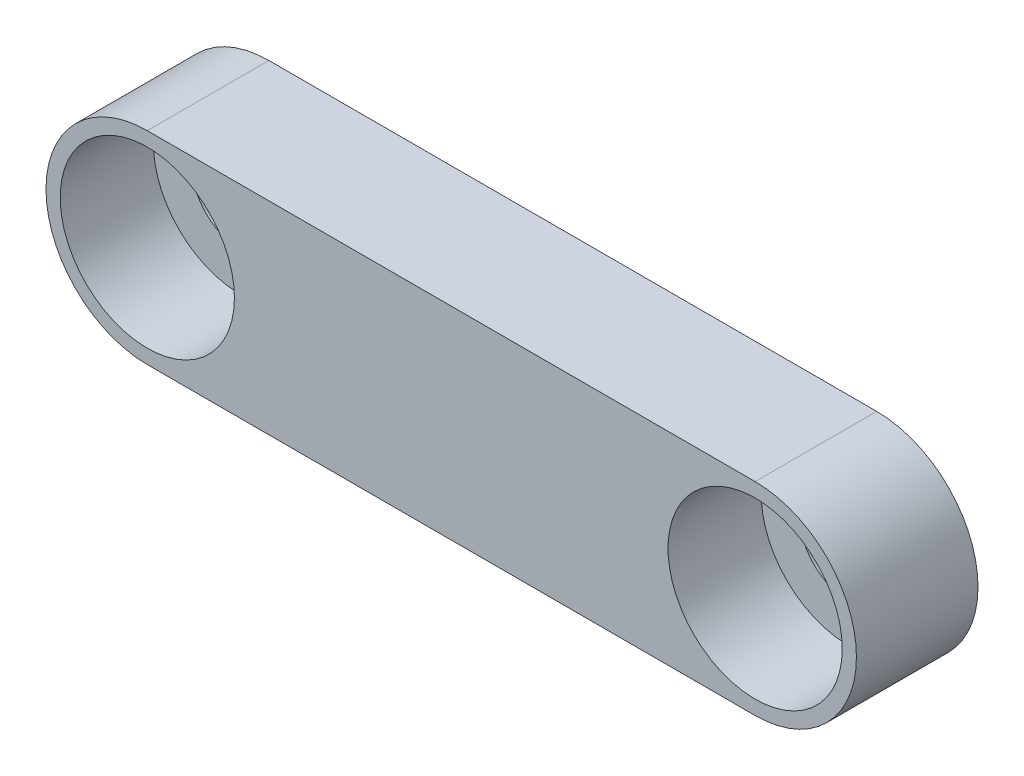
SolidWorks part; units mm, degrees
material "PLA MATTE"
ref_plane "前视基准面" through (0, 0, 0) normal (0, 0, 1) x (1, 0, 0)
ref_plane "上视基准面" through (0, 0, 0) normal (0, 1, 0) x (1, 0, 0)
ref_plane "右视基准面" through (0, 0, 0) normal (1, 0, 0) x (0, 0, -1)
sketch "草图1" plane through (0, 0, 0) normal (0, 0, 1) x (1, 0, 0)
  line L0 (-7.5, 0) -> (7.5, 0) construction
  line L1 (-7.5, 2.5) -> (7.5, 2.5)
  line L2 (-7.5, -2.5) -> (7.5, -2.5)
  arc A0 (-7.5, 2.5) -> (-7.5, -2.5) centre (-7.5, 0) ccw
  arc A1 (7.5, -2.5) -> (7.5, 2.5) centre (7.5, 0) ccw
  point P2 (0, 0)
  dimension "D1" = 15
  dimension "D2" = 5
extrude "凸台-拉伸1" add sketch "草图1" along normal blind 3
hole_wizard "打孔尺寸(%根据)内六角圆柱头螺钉的类型1" positions "草图2" profile "草图3" counterbore size "M2" standard "GB"
sketch "草图2" plane through (0, 0, 3) normal (0, 0, 1) x (1, 0, 0)
  point P0 (-7.5, 0)
  point P3 (7.5, 0)
sketch "草图3" plane through (-7.5, 0, 3) normal (1, 0, 0) x (0, -1, 0)
  line L0 (0, 0) -> (0, 5.921)
  line L1 (0, 5.921) -> (1.2, 5.2)
  line L2 (1.2, 5.2) -> (1.2, 2.3)
  line L3 (1.2, 2.3) -> (2.15, 2.3)
  line L4 (2.15, 2.3) -> (2.15, 0)
  line L5 (2.15, 0) -> (0, 0)
  line L10 (0, 5.921) -> (-1.2, 5.2) construction
  line L11 (0, -6.35) -> (0, 107.95) construction
  dimension "孔直径" = 2.4
  dimension "孔深度" = 5.2
  dimension "柱形沉头孔直径" = 4.3
  dimension "柱形沉头孔深度" = 2.3
  dimension "导头角度" = 118
